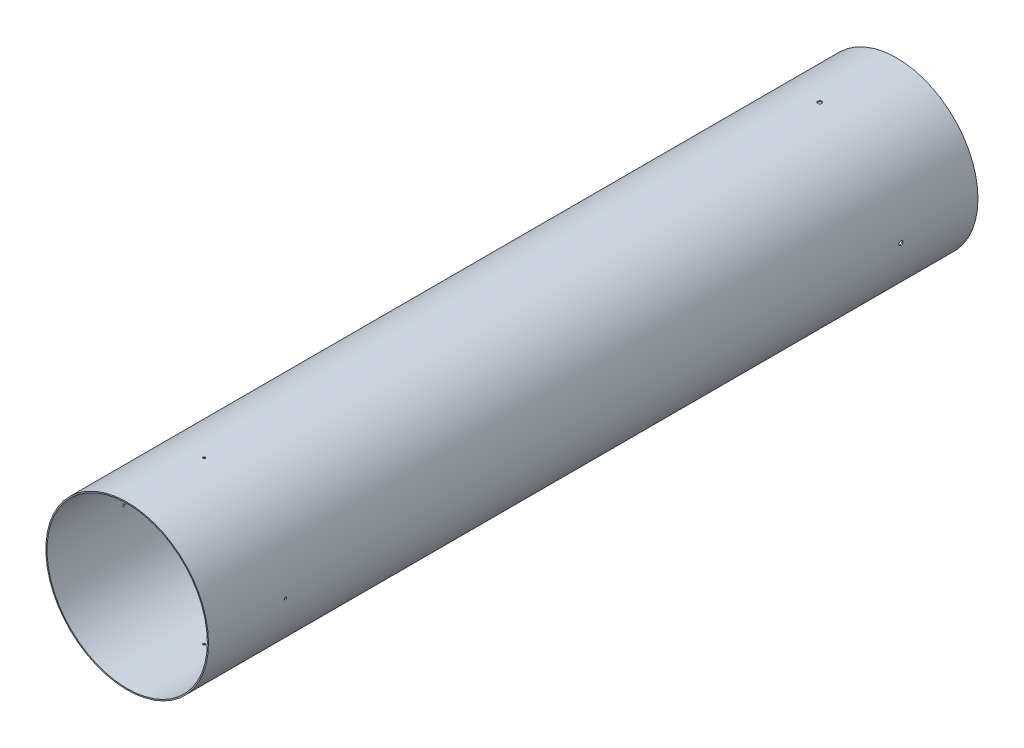
SolidWorks part; units mm, degrees
ref_plane "Front Plane" through (0, 0, 0) normal (0, 0, 1) x (1, 0, 0)
ref_plane "Top Plane" through (0, 0, 0) normal (0, 1, 0) x (1, 0, 0)
ref_plane "Right Plane" through (0, 0, 0) normal (1, 0, 0) x (0, 0, -1)
sketch "Sketch1" plane through (0, 0, 0) normal (0, 0, 1) x (1, 0, 0)
  circle A0 centre (0, 0) radius 79.375
  circle A1 centre (0, 0) radius 80.518
  dimension "D1" = 158.75
  dimension "D2" = 1.143
extrude "Boss-Extrude1" add sketch "Sketch1" along normal blind 762
ref_plane "Plane1" through (0, 80.518, 0) normal (0, 1, 0) x (1, 0, 0)
sketch "Sketch2" plane through (0, 80.518, 0) normal (0, 1, 0) x (1, 0, 0)
  line L0 (80.518, 0) -> (-80.518, 0) construction
  point P0 (0, -76.2)
  dimension "D1" = 76.2
hole_wizard "Tap Drill for #10-32 Tap1" positions "Sketch3" profile "Sketch4" hole size "#10-32" standard "ANSI Inch"
sketch "Sketch3" plane through (0, 80.518, 0) normal (0, 1, 0) x (1, 0, 0)
  point P0 (0, -76.2)
sketch "Sketch4" plane through (0, 80.518, 76.2) normal (1, 0, 0) x (0, 0, 1)
  line L0 (0, 0) -> (0, 1.143)
  line L1 (0, 1.143) -> (2.0193, 1.143)
  line L2 (2.0193, 1.143) -> (2.0193, 0)
  line L5 (2.0193, 0) -> (0, 0)
  line L11 (0, -6.35) -> (0, 107.95) construction
  dimension "Thru Hole Dia." = 4.0386
  dimension "Thru Hole Depth" = 1.143
sketch "Sketch5" plane through (0, 80.518, 0) normal (0, 1, 0) x (1, 0, 0)
  line L0 (-80.518, -762) -> (80.518, -762) construction
  point P0 (0, -685.8)
  point P3 (0, 0)
  dimension "D1" = 76.2
hole_wizard "Tap Drill for #4-40 Tap1" positions "Sketch6" profile "Sketch7" hole size "#4-40" standard "ANSI Inch"
sketch "Sketch6" plane through (0, 80.518, 0) normal (0, 1, 0) x (1, 0, 0)
  point P0 (0, -685.8)
sketch "Sketch7" plane through (0, 80.518, 685.8) normal (1, 0, 0) x (0, 0, 1)
  line L0 (0, 0) -> (0, 1.143)
  line L1 (0, 1.143) -> (1.1303, 1.143)
  line L2 (1.1303, 1.143) -> (1.1303, 0)
  line L5 (1.1303, 0) -> (0, 0)
  line L11 (0, -6.35) -> (0, 107.95) construction
  dimension "Thru Hole Dia." = 2.2606
  dimension "Thru Hole Depth" = 1.143
pattern_circular "CirPattern1" count 4 over 360 about axis through (0, 0, 762) along (0, 0, 1) of "Tap Drill for #10-32 Tap1", "Tap Drill for #4-40 Tap1"
